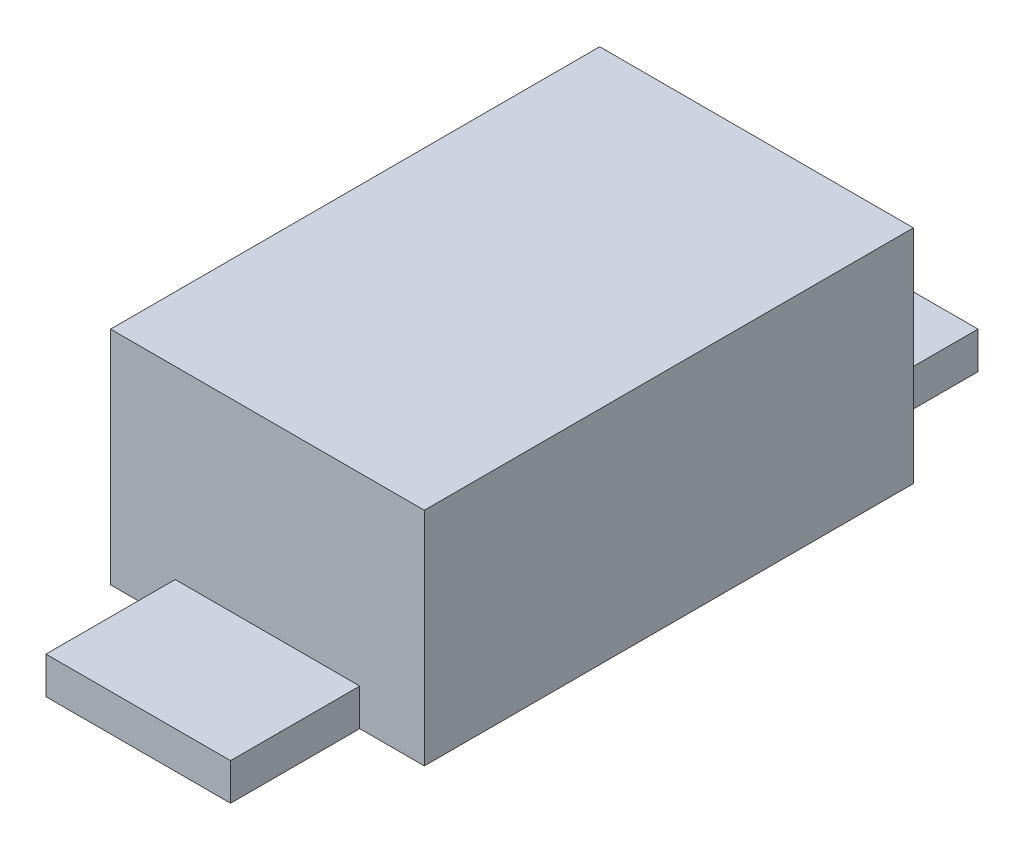
SolidWorks part; units mm, degrees
ref_plane "Piano frontale" through (0, 0, 0) normal (0, 0, 1) x (1, 0, 0)
ref_plane "Piano superiore" through (0, 0, 0) normal (0, 1, 0) x (1, 0, 0)
ref_plane "Piano destro" through (0, 0, 0) normal (1, 0, 0) x (0, 0, -1)
sketch "Schizzo1" plane through (0, 0, 0) normal (0, 1, 0) x (1, 0, 0)
  line L1 (-6.8982, -7.1225) -> (-5.1982, -7.1225)
  line L2 (-6.8982, -7.1225) -> (-6.8982, -9.7725)
  line L3 (-6.8982, -9.7725) -> (-5.1982, -9.7725)
  line L4 (-5.1982, -7.1225) -> (-5.1982, -9.7725)
  dimension "D1" = 2.65
  dimension "D2" = 1.7
extrude "Estrusione-Estrusione1" add sketch "Schizzo1" along normal blind 1.2
sketch "Schizzo2" plane through (0, 0, 9.7725) normal (0, 0, 1) x (1, 0, 0)
  line L0 (-6.8982, 0) -> (-5.1982, 0) construction
  line L1 (-6.5482, 0) -> (-5.5482, 0)
  line L2 (-6.5482, 0) -> (-6.5482, 0.2)
  line L3 (-6.5482, 0.2) -> (-5.5482, 0.2)
  line L4 (-5.5482, 0) -> (-5.5482, 0.2)
  line L5 (-6.8982, 1.2) -> (-6.8982, 0) construction
  dimension "D1" = 1
  dimension "D2" = 0.2
  dimension "D3" = 0.35
extrude "Estrusione-Estrusione2" add sketch "Schizzo2" along normal blind 0.7
sketch "Schizzo4" plane through (0, 0, 7.1225) normal (0, 0, -1) x (-1, 0, 0)
  line L0 (5.5482, 0) -> (6.5482, 0)
  line L1 (5.5482, 0) -> (5.5482, 0.2)
  line L2 (5.5482, 0.2) -> (6.5482, 0.2)
  line L3 (6.5482, 0) -> (6.5482, 0.2)
  line L4 (5.1982, 0) -> (6.8982, 0) construction
  line L5 (5.1982, 1.2) -> (5.1982, 0) construction
  line L6 (6.8982, 1.2) -> (6.8982, 0) construction
  dimension "D1" = 0
  dimension "D2" = 0.35
  dimension "D3" = 0.35
extrude "Estrusione-Estrusione4" add sketch "Schizzo4" along normal blind 0.7
